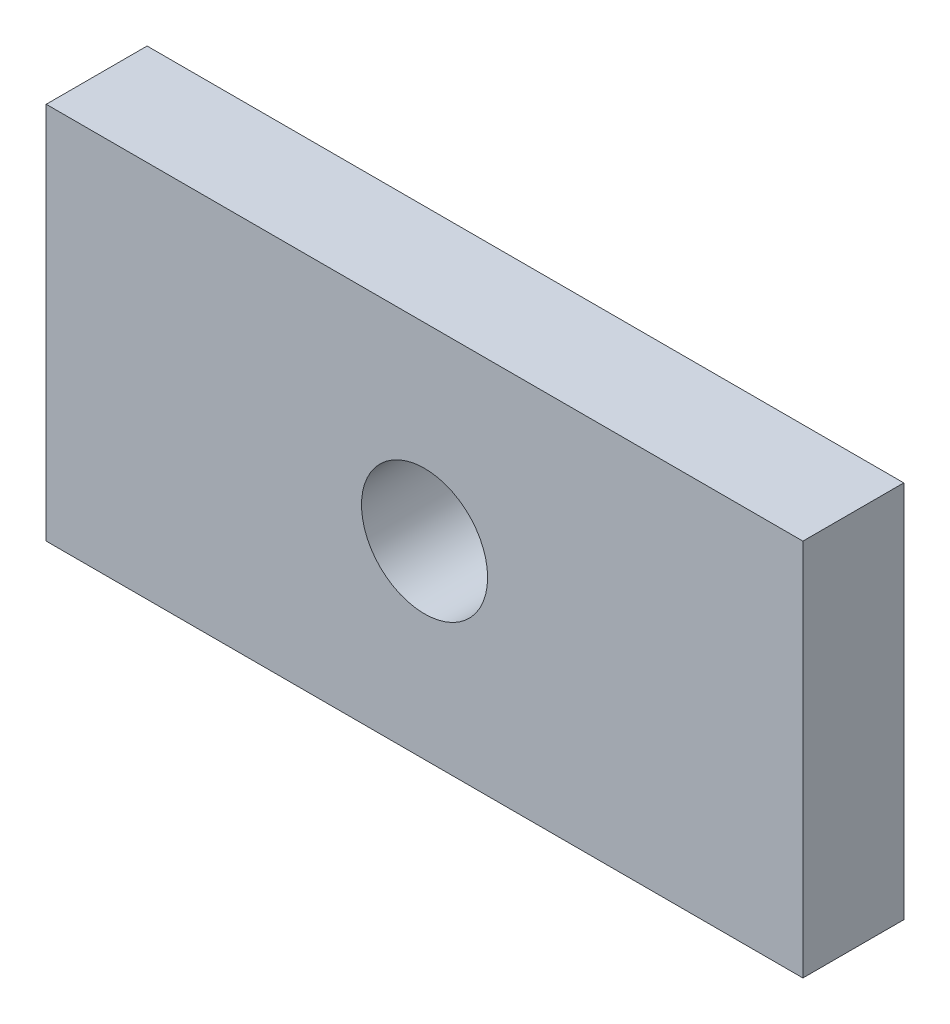
SolidWorks part; units mm, degrees
material "AISI 304"
ref_plane "Front" through (0, 0, 0) normal (0, 0, 1) x (1, 0, 0)
ref_plane "Top" through (0, 0, 0) normal (0, 1, 0) x (1, 0, 0)
ref_plane "Right" through (0, 0, 0) normal (1, 0, 0) x (0, 0, -1)
sketch "草图2" plane through (0, 0, 0) normal (0, 0, 1) x (1, 0, 0)
  line L1 (-150, -75) -> (150, -75)
  line L2 (-150, -75) -> (-150, 75)
  line L3 (-150, 75) -> (150, 75)
  line L4 (150, -75) -> (150, 75)
  line L5 (-150, -75) -> (150, 75) construction
  line L6 (-150, 75) -> (150, -75) construction
  point P0 (0, 0)
  dimension "D1" = 300
  dimension "D2" = 150
extrude "凸台-拉伸1" add sketch "草图2" along normal blind 40
sketch "草图3" plane through (0, 0, 40) normal (0, 0, 1) x (1, 0, 0)
  circle A0 centre (0, 0) radius 25
  dimension "D1" = 50
extrude "切除-拉伸1" cut sketch "草图3" against normal blind 40
